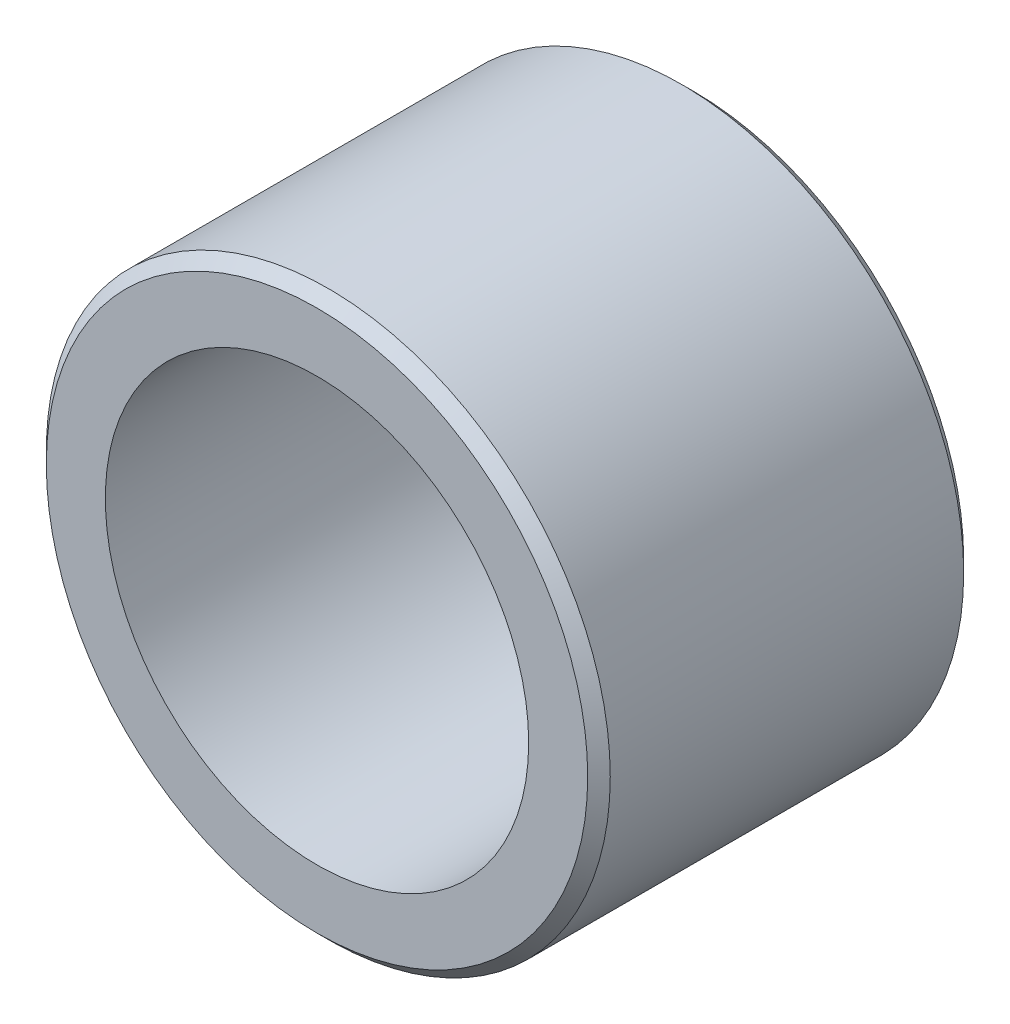
SolidWorks part; units mm, degrees
material "Brass"
ref_plane "Front" through (0, 0, 0) normal (0, 0, 1) x (1, 0, 0)
ref_plane "Top" through (0, 0, 0) normal (0, 1, 0) x (1, 0, 0)
ref_plane "Right" through (0, 0, 0) normal (1, 0, 0) x (0, 0, -1)
sketch "Sketch1" plane through (0, 0, 0) normal (0, 0, 1) x (1, 0, 0)
  circle A0 centre (0, 0) radius 9.525
  circle A1 centre (0, 0) radius 7.1501
  dimension "D1" = 14.3002
  dimension "D2" = 19.05
extrude "Boss-Extrude1" add sketch "Sketch1" along normal mid plane 12.7
chamfer "Chamfer1" distance 0.381 angle 45 2 edges at (9.525, 0, -6.35) (9.525, 0, 6.35)
